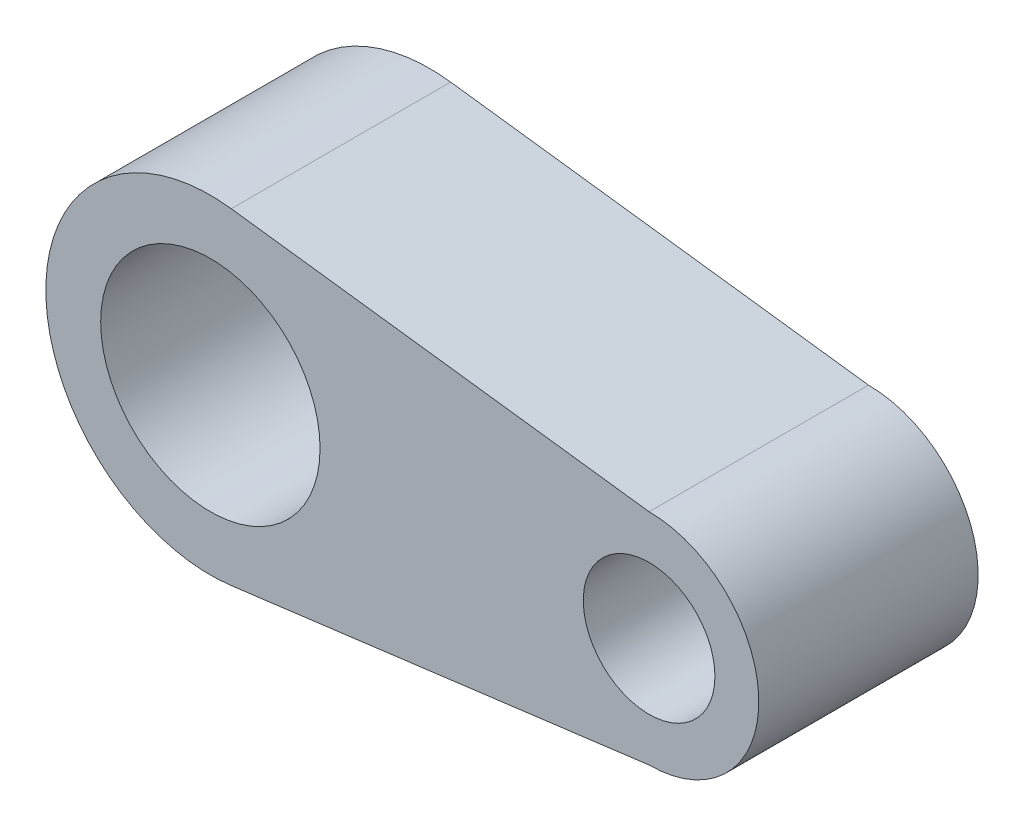
SolidWorks part; units mm, degrees
ref_plane "Front Plane" through (0, 0, 0) normal (0, 0, 1) x (1, 0, 0)
ref_plane "Top Plane" through (0, 0, 0) normal (0, 1, 0) x (1, 0, 0)
ref_plane "Right Plane" through (0, 0, 0) normal (1, 0, 0) x (0, 0, -1)
sketch "Sketch1" plane through (0, 0, 0) normal (0, 0, 1) x (1, 0, 0)
  line L0 (0, 0) -> (20, 0) construction
  line L1 (20, 5) -> (0.9527, 7.4392)
  line L2 (20, -5) -> (0.9527, -7.4392)
  circle A0 centre (0, 0) radius 5
  circle A1 centre (0, 0) radius 7.5
  circle A2 centre (20, 0) radius 5
  circle A3 centre (20, 0) radius 3
  dimension "D1" = 10
  dimension "D2" = 15
  dimension "D4" = 10
  dimension "D5" = 6
  dimension "D3" = 20
extrude "Boss-Extrude1" add sketch "Sketch1" along normal blind 10
